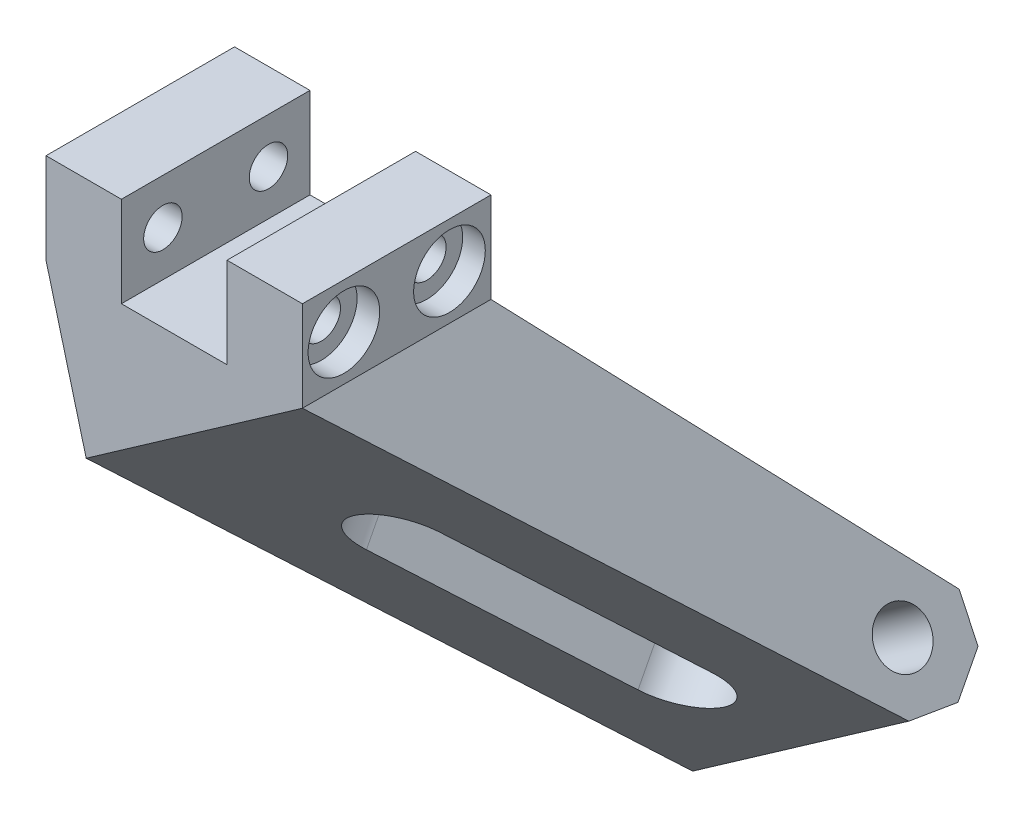
SolidWorks part; units mm, degrees
material "1060 合金"
ref_plane "前视基准面" through (0, 0, 0) normal (0, 0, 1) x (1, 0, 0)
ref_plane "上视基准面" through (0, 0, 0) normal (0, 1, 0) x (1, 0, 0)
ref_plane "右视基准面" through (0, 0, 0) normal (1, 0, 0) x (0, 0, -1)
sketch "草图1" plane through (0, 0, 0) normal (0, 0, 1) x (1, 0, 0)
  line L0 (0, 0) -> (0, 16.0634) construction
  line L1 (0, 0) -> (23.6571, 0) construction
  line L2 (-7, 0) -> (-17, 12) construction
  line L3 (7, 12) -> (17, 12)
  line L4 (7, 12) -> (7, 0)
  line L5 (7, 0) -> (17, 0)
  line L6 (17, 12) -> (17, 0)
  line L7 (7, 12) -> (17, 0) construction
  line L8 (7, 0) -> (17, 12) construction
  line L9 (-7, 12) -> (-17, 0) construction
  line L10 (-17, 12) -> (-17, 0)
  line L11 (-7, 0) -> (-17, 0)
  line L12 (-7, 12) -> (-7, 0)
  line L13 (-7, 12) -> (-17, 12)
  point P3 (12, 6)
  point P13 (-12, 6)
  dimension "D1" = 14
  dimension "D2" = 10
  dimension "D3" = 12
extrude "凸台-拉伸1" add sketch "草图1" along normal mid plane 25
hole_wizard "打孔尺寸(%根据)内六角圆柱头螺钉的类型1" positions "草图3" profile "草图2" counterbore size "M5" standard "GB" end condition through all
sketch "草图3" plane through (17, 0, 0) normal (-1, 0, 0) x (0, 0, 1)
  line L0 (0, 0) -> (0, 14.2951) construction
  line L1 (12.5, 0) -> (-12.5, 0) construction
  line L3 (-12.5, 6) -> (-7, 6) construction
  line L4 (-12.5, 12) -> (-12.5, 0) construction
  point P2 (-7, 6)
  point P4 (7, 6)
  dimension "D1" = 14
sketch "草图2" plane through (17, 6, -7) normal (0, 1, 0) x (0, 0, -1)
  line L0 (0, 0) -> (0, 34)
  line L1 (0, 34) -> (2.55, 34)
  line L3 (2.55, 34) -> (2.55, 3)
  line L4 (2.55, 3) -> (4.75, 3)
  line L5 (4.75, 3) -> (4.75, 0)
  line L7 (4.75, 0) -> (0, 0)
  line L11 (0, -6.35) -> (0, 107.95) construction
  dimension "通孔孔直径" = 5.1
  dimension "通孔孔深度" = 34
  dimension "柱形沉头孔直径" = 9.5
  dimension "柱形沉头孔深度" = 3
sketch "草图6" plane through (0, 0, -12.5) normal (0, 0, -1) x (-1, 0, 0)
  line L0 (-17, 0) -> (17, 0)
  line L1 (17, 0) -> (11.6703, -20.0752)
  line L2 (11.6703, -20.0752) -> (-17, 0)
  dimension "D1" = 35
  dimension "D2" = 35
extrude "凸台-拉伸4" add sketch "草图6" against normal up to surface (25 mm away) up to face at (12, 6, 12.5)
ref_plane "基准面1" through (-2.928, -2.0502, 0) normal (-0.8192, -0.5736, 0) x (0, 0, 1)
sketch "草图4" plane through (-7.6854, 4.744, 0) normal (-0.8192, -0.5736, 0) x (0, 0, -1)
  line L2 (12.5, 18.045) -> (50.5393, 67.3947)
  line L3 (50.5393, 67.3947) -> (39.451, 75.9416)
  line L4 (39.451, 75.9416) -> (-12.5, 18.045)
  line L5 (44.9951, 71.6681) -> (0, 18.045) construction
  line L6 (-12.5, 18.045) -> (12.5, 18.045)
  circle A0 centre (39.8484, 65.5345) radius 3.5
  dimension "D3" = 7
  dimension "D1" = 70
  dimension "D2" = 50
  dimension "D4" = 14
  dimension "D5" = 8
extrude "凸台-拉伸2" add sketch "草图4" along normal up to vertex (17.5 mm away) and the other way up to vertex (17.5 mm away)
sketch "草图5" plane through (-1.1689, 1.6046, -3.454) normal (0.3502, -0.5001, 0.792) x (-0.9325, -0.1064, 0.3451)
  line L0 (-40.682, 65.6195) -> (3.1694, 1.6325) construction
  line L1 (-26.2465, 75.5123) -> (-55.1174, 55.7266) construction
  line L2 (-29.6585, 49.5343) -> (-11.1116, 22.471) construction
  line L3 (-24.7092, 52.9261) -> (-6.1623, 25.8629)
  line L4 (-34.6078, 46.1425) -> (-16.0609, 19.0792)
  line L7 (-11.266, -8.2603) -> (17.6048, 11.5254) construction
  line L9 (-48.6164, 46.2405) -> (-19.7455, 66.0262) construction
  line L10 (-19.894, 4.3294) -> (8.9769, 24.1151) construction
  arc A0 (-24.7092, 52.9261) -> (-34.6078, 46.1425) centre (-29.6585, 49.5343) ccw
  arc A1 (-16.0609, 19.0792) -> (-6.1623, 25.8629) centre (-11.1116, 22.471) ccw
  point P7 (-20.385, 36.0027)
  dimension "D1" = 8
  dimension "D3" = 10
  dimension "D2" = 12
extrude "切除-拉伸1" cut sketch "草图5" along normal up to next
chamfer "倒角1" distance 4 angle 45 2 edges at (35.873, -57.4637, -39.451) (30.9706, -50.4624, -50.5393)
hole_wizard "M3 螺纹孔1" positions "草图8" profile "草图7" tap size "M3" standard "GB"
sketch "草图8" plane through (-17.2632, -12.0878, 0) normal (-0.8192, -0.5736, 0) x (0, 0, 1)
  line L0 (-39.8484, -57.2403) -> (24.228, 14.1694) construction
  line L4 (-36.5556, -64.4206) -> (12.5, -9.7508) construction
  line L5 (2.6109, -20.7716) -> (-7.0797, -12.0762) construction
  point P0 (0.223, -12.5829)
  point P2 (-5.7877, -19.2815)
  dimension "D1" = 9
  dimension "D2" = 55.5
sketch "草图7" plane through (-10.0459, -22.3951, 0.223) normal (0, 0, 1) x (0.5736, -0.8192, 0)
  line L0 (0, 0) -> (0, 9.2511)
  line L1 (0, 9.2511) -> (1.25, 8.5)
  line L2 (1.25, 8.5) -> (1.25, 0)
  line L5 (1.25, 0) -> (0, 0)
  line L10 (0, 9.2511) -> (-1.25, 8.5) construction
  line L11 (0, -6.35) -> (0, 107.95) construction
  dimension "螺纹孔钻头直径" = 2.5
  dimension "螺纹孔钻头深度" = 8.5
  dimension "导头角度" = 118
cosmetic thread "孔螺蚊线1" parameters "D1"=6, "D2"=3
cosmetic thread "孔螺蚊线2" parameters "D1"=6, "D2"=3
sketch "草图11" plane through (-17.2632, -12.0878, 0) normal (-0.8192, -0.5736, 0) x (0, 0, 1)
  line L0 (-5.7877, -19.2815) -> (-69.1492, 29.5583) construction
  line L2 (-12.5, -9.7508) -> (-48.0973, -55.9324) construction
  point P0 (-69.1492, 29.5583)
  dimension "D1" = 80
  dimension "D2" = 91.6107
ref_point "点1"
move or copy body "实体-移动/复制1" [suppressed] bodies to move or copy 113
